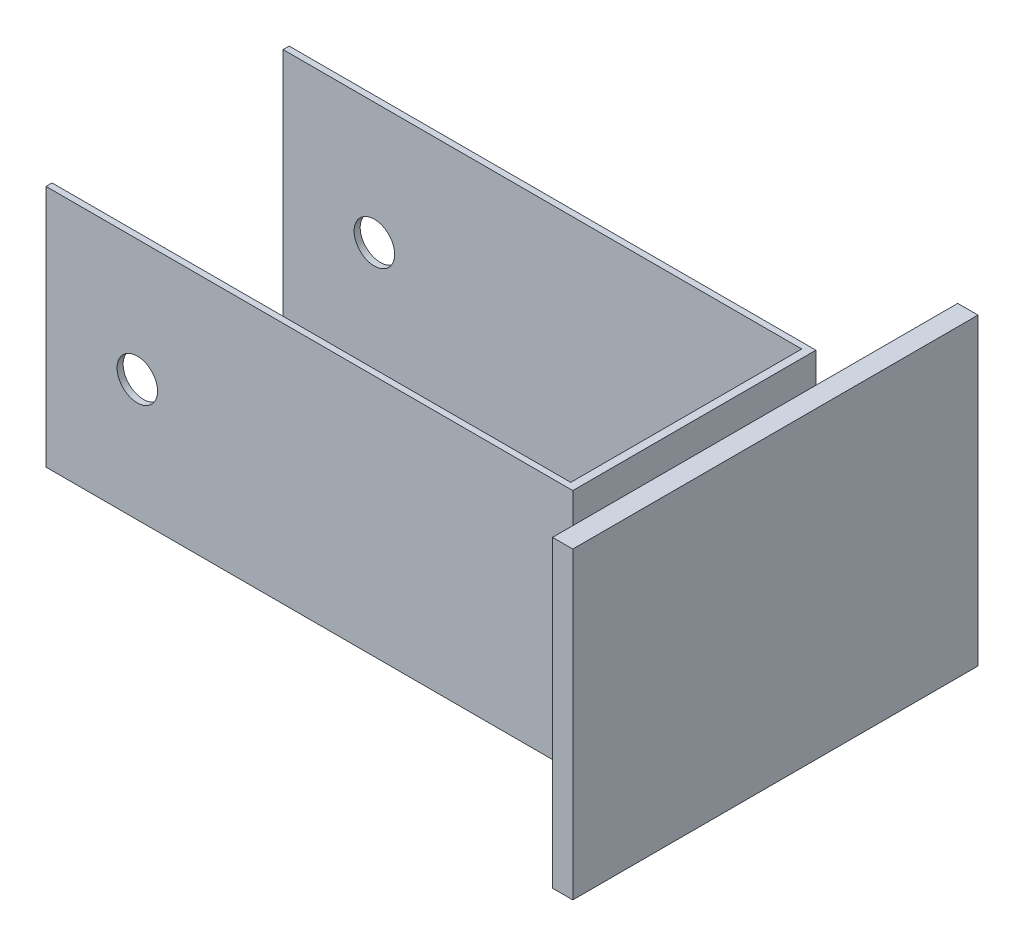
SolidWorks part; units mm, degrees
ref_plane "Plano frontal" through (0, 0, 0) normal (0, 0, 1) x (1, 0, 0)
ref_plane "Plano superior" through (0, 0, 0) normal (0, 1, 0) x (1, 0, 0)
ref_plane "Plano direito" through (0, 0, 0) normal (1, 0, 0) x (0, 0, -1)
sketch "Esboço1" plane through (0, 0, 0) normal (0, 0, 1) x (1, 0, 0)
  line L1 (65, 30) -> (-65, 30)
  line L3 (65, -30) -> (-65, -30)
  line L4 (-65, 30) -> (-65, -30)
  line L5 (65, 30) -> (-65, -30) construction
  line L6 (65, -30) -> (-65, 30) construction
  arc A0 (65, 30) -> (130.9931, 0) centre (65, -57.5849) cw
  arc A1 (65, -30) -> (130.9931, 0) centre (65, 57.5849) ccw
  point P0 (0, 0)
  dimension "D1" = 130
extrude "Ressalto-extrusão1" add sketch "Esboço1" along normal blind 60
sketch "Esboço3" plane through (0, 0, 0) normal (0, 0, 1) x (1, 0, 0)
  line L0 (65, 25) -> (65, -25)
  arc A0 (65, 25) -> (104.3393, 0) centre (65, -18.4516) cw
  arc A1 (65, -25) -> (104.3393, 0) centre (65, 18.4516) ccw
  dimension "D1" = 5
  dimension "D2" = 5
extrude "Corte-extrusão1" cut sketch "Esboço3" against normal through all and the other way through all
sketch "Esboço5" plane through (0, 0, 0) normal (0, 1, 0) x (1, 0, 0)
  line L0 (65, 0) -> (-65, 0) construction
  line L1 (63, -1.5) -> (-63, -1.5)
  line L2 (63, -1.5) -> (63, -58.5)
  line L3 (63, -58.5) -> (-63, -58.5)
  line L4 (-63, -1.5) -> (-63, -58.5)
  line L5 (63, -1.5) -> (-63, -58.5) construction
  line L6 (63, -58.5) -> (-63, -1.5) construction
  line L7 (65, -60) -> (-65, -60) construction
  line L8 (-65, -60) -> (-65, 0) construction
  line L9 (65, -60) -> (65, 0) construction
  point P0 (0, -30)
  dimension "D1" = 1.5
  dimension "D2" = 1.5
  dimension "D3" = 2
  dimension "D4" = 2
extrude "Corte-extrusão2" cut sketch "Esboço5" against normal through all both and the other way through all
sketch "Esboço6" plane through (-63, 0, 0) normal (1, 0, 0) x (0, 0, -1)
  line L1 (-1.5, -30) -> (-58.5, -30)
  line L2 (-1.5, -30) -> (-1.5, 30)
  line L3 (-1.5, 30) -> (-58.5, 30)
  line L4 (-58.5, -30) -> (-58.5, 30)
extrude "Corte-extrusão3" cut sketch "Esboço6" against normal blind 57
sketch "Esboço7" plane through (0, 0, 0) normal (0, 0, 1) x (1, 0, 0)
  circle A0 centre (-42.467, 0) radius 5
  dimension "D1" = 10
extrude "Corte-extrusão4" cut sketch "Esboço7" against normal blind 57 and the other way through all
sketch "Esboço8" plane through (0, 0, 0) normal (0, 1, 0) x (1, 0, 0)
  line L1 (65, 0) -> (130.9931, 0)
  line L2 (65, 0) -> (65, -60)
  line L3 (65, -60) -> (130.9931, -60)
  line L4 (130.9931, 0) -> (130.9931, -60)
extrude "Corte-extrusão5" cut sketch "Esboço8" along normal through all both and the other way through all
sketch "Esboço13" plane through (65, 0, 0) normal (1, 0, 0) x (0, 0, -1)
  circle A0 centre (-30, 0) radius 15
  dimension "D1" = 30
extrude "Ressalto-extrusão2" add sketch "Esboço13" along normal blind 15
sketch "Esboço14" plane through (80, 0, 0) normal (1, 0, 0) x (0, 0, -1)
  line L1 (20, 37.5) -> (-80, 37.5)
  line L2 (20, 37.5) -> (20, -37.5)
  line L3 (20, -37.5) -> (-80, -37.5)
  line L4 (-80, 37.5) -> (-80, -37.5)
  line L5 (20, 37.5) -> (-80, -37.5) construction
  line L6 (20, -37.5) -> (-80, 37.5) construction
  point P0 (-30, 0)
  dimension "D1" = 100
  dimension "D2" = 75
extrude "Ressalto-extrusão3" add sketch "Esboço14" along normal blind 5
